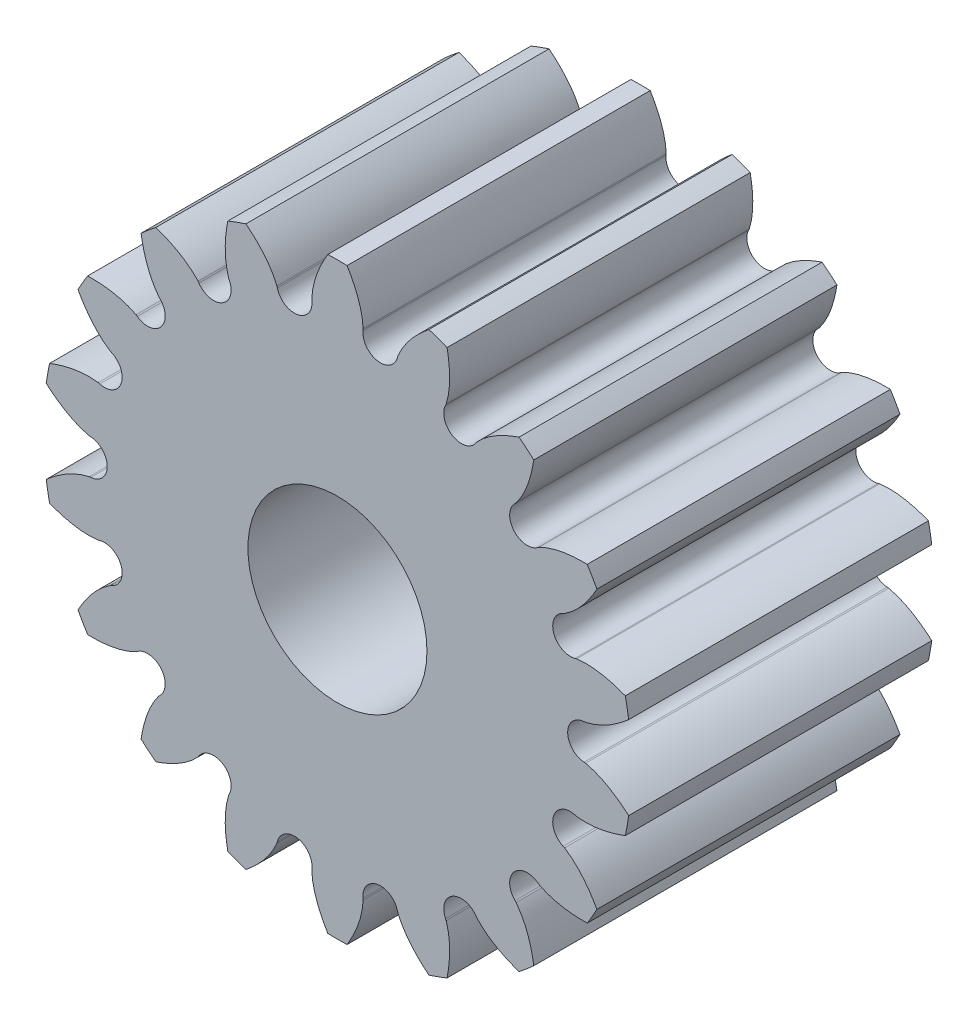
SolidWorks part; units mm, degrees
material "PE Low/Medium Density"
ref_plane "Front Plane" through (0, 0, 0) normal (0, 0, 1) x (1, 0, 0)
ref_plane "Top Plane" through (0, 0, 0) normal (0, 1, 0) x (1, 0, 0)
ref_plane "Right Plane" through (0, 0, 0) normal (1, 0, 0) x (0, 0, -1)
sketch "Involute construction sketch" plane through (0, 0, 0) normal (0, 0, 1) x (1, 0, 0)
  line L0 (0, 0) -> (-1.8157, 1.6751) construction
  line L1 (0, 0) -> (-1.2188, 2.1487) construction
  line L2 (0, 0) -> (-0.506, 2.418) construction
  line L3 (0, 0) -> (0.255, 2.4572) construction
  line L4 (-2.4509, 0.3098) -> (-2.2398, 1.042) construction
  line L5 (-2.2398, 1.042) -> (-1.8157, 1.6751) construction
  line L6 (-1.8157, 1.6751) -> (-1.2188, 2.1487) construction
  line L7 (0, 0) -> (-2.2398, 1.042) construction
  line L8 (0, 0) -> (-2.4509, 0.3098) construction
  line L9 (-1.2188, 2.1487) -> (-0.506, 2.418) construction
  line L10 (-0.506, 2.418) -> (0.255, 2.4572) construction
  line L11 (-2.4509, 0.3098) -> (-1.9731, 4.0897) construction
  line L12 (-2.2398, 1.042) -> (-0.9542, 3.8056) construction
  line L13 (-1.8157, 1.6751) -> (-0.2657, 3.3553) construction
  line L14 (-1.2188, 2.1487) -> (0.1068, 2.9007) construction
  line L15 (-0.506, 2.418) -> (0.2399, 2.5741) construction
  line L17 (0, 0) -> (0, 5.7859) construction
  line L18 (0, 0) -> (0.2291, 2.6189) construction
  line L19 (0, 0) -> (0.397, 2.2513) construction
  circle A0 centre (0, 0) radius 2.286 construction
  circle A1 centre (0, 0) radius 2.4704 construction
  circle A2 centre (0, 0) radius 2.6289 construction
  circle A3 centre (0, 0) radius 2.921 construction
  spline S0 degree 3 poles (0.255, 2.4572) (0.2476, 2.615) (0.11, 2.9502) (-0.5314, 3.7068) (-1.3595, 4.0133) (-1.9731, 4.0897) knots 0 0 0 0 0.160126 0.360107 1 1 1 1 construction
  point P17 (0.0957, 2.9194)
  dimension "D1" = 4.572
  dimension "D2" = 4.9407
  dimension "D3" = 5.2578
  dimension "D4" = 5.842
  dimension "D5" = 0.762
  dimension "D6" = 1.524
  dimension "D7" = 2.286
  dimension "D8" = 3.048
  dimension "D9" = 3.81
  dimension "D10" = 5
  dimension "D11" = 10
sketch "Sketch2" plane through (0, 0, 0) normal (0, 0, 1) x (1, 0, 0)
  line L0 (0, 2.921) -> (0, 2.286)
  line L1 (0, 0) -> (0, 5.7859) construction
  line L2 (0.255, 2.4572) -> (0.2534, 2.4415)
  line L3 (0, 0) -> (0.255, 2.4572) construction
  circle A0 centre (0, 0) radius 2.921 construction
  circle A1 centre (0, 0) radius 2.286 construction
  arc A2 (0, 2.921) -> (0.0957, 2.9194) centre (0, 0) cw
  arc A3 (0, 2.286) -> (0.397, 2.2513) centre (0, 0) cw
  arc A4 (0.2534, 2.4415) -> (0.397, 2.2513) centre (0.4273, 2.4235) ccw
  spline S0 degree 3 poles (0.255, 2.4572) (0.2525, 2.512) (0.2249, 2.6747) (0.152, 2.8255) (0.0957, 2.9194) knots 0 0 0 0 0.332628 1 1 1 1
sketch "Sketch3" plane through (0, 0, 0) normal (0, 0, 1) x (1, 0, 0)
  circle A0 centre (0, 0) radius 2.286
  circle A1 centre (0, 0) radius 0.889
  dimension "D1" = 4.572
  dimension "D2" = 1.778
extrude "Base" add sketch "Sketch3" along normal blind 3.0099
extrude "Half tooth" add sketch "Sketch2" along normal up to surface (3.0099 mm away) up to face at (2.286, 0, 3.0099)
ref_plane "Midplane of half tooth" through (0, 0, 0) normal (-1, 0, 0) x (0, 0, 1)
mirror "Mirror of half tooth" about plane through (0, 0, 0) normal (-1, 0, 0) of "Half tooth"
pattern_circular "Pattern of half tooth" count 18 over 360 of "Half tooth", "Mirror of half tooth"
equation "\"radtodeg\"= 180 / PI'radian to degree conversion [ ]"
equation "\"phi\"= 20'pressure angle [deg]"
equation "\"N\"= 18'number of teeth [teeth]"
equation "\"A\"= 0.230in'diameter of addendum circle [inch]"
equation "\"B\"= 0.18in'diameter of dedendum circle [inch]"
equation "\"P\"= ( \"N\" + 2 ) / \"A\"'diametral pitch [teeth/inch]"
equation "\"d\"= \"N\" / \"P\"'diameter of pitch circle [inch]"
equation "\"cp\"= PI / \"P\"'circular pitch [inch/teeth]"
equation "\"add\"= 1 / \"P\"'addendum [inch]"
equation "\"ded\"= - ( \"B\" - \"d\" ) / 2'dedendum [inch]"
equation "\"clear\"= \"ded\" - \"add\"'clearance [inch]"
equation "\"C\"= \"B\" + 2 * \"clear\"'diameter of clearance circle [inch]"
equation "\"h\"= \"add\" + \"ded\"'tooth height / whole depth [inch]"
equation "\"s\"= \"d\" * cos ( \"phi\" * 1 / \"radtodeg\" )'diameter of base circle [inch]"
equation "\"t\"= ( PI / 2 ) / \"P\"'tooth width at diameter of pitch circle diameter [inch]"
equation "\"alpha\"= ( \"t\" / ( \"d\" / 2 ) * \"radtodeg\" ) / 2'arc angle for half of tooth width at pitch circle diameter [inch]"
equation "\"bore\"= 0.07'bore of hub [inch]"
equation "\"D4@Involute construction sketch\"= \"A\"'addendum circle"
equation "\"D3@Involute construction sketch\"= \"d\"'pitch circle"
equation "\"D2@Involute construction sketch\"= \"s\"'base circle"
equation "\"D1@Involute construction sketch\"= \"B\"'dedendum circle"
equation "\"seg\"= \"D5@Involute construction sketch\"'size of one involute segment [inch]"
equation "\"D6@Involute construction sketch\"=2*\"seg\""
equation "\"D7@Involute construction sketch\"=3*\"seg\""
equation "\"D8@Involute construction sketch\"=4*\"seg\""
equation "\"D9@Involute construction sketch\"=5*\"seg\""
equation "\"D10@Involute construction sketch\"=\"alpha\""
equation "\"D11@Involute construction sketch\"=2*\"alpha\""
equation "\"D1@Sketch3\"=\"B\""
equation "\"D2@Sketch3\"=\"bore\""
